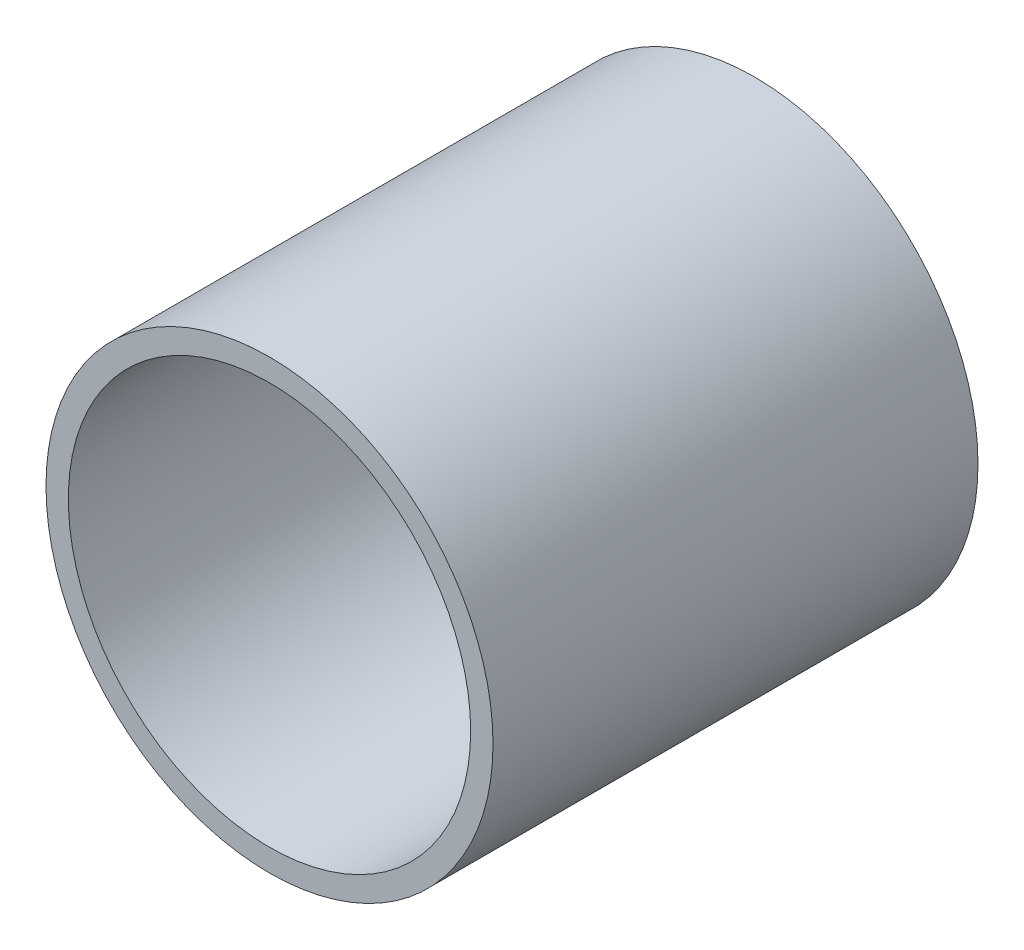
SolidWorks part; units mm, degrees
ref_plane "Front Plane" through (0, 0, 0) normal (0, 0, 1) x (1, 0, 0)
ref_plane "Top Plane" through (0, 0, 0) normal (0, 1, 0) x (1, 0, 0)
ref_plane "Right Plane" through (0, 0, 0) normal (1, 0, 0) x (0, 0, -1)
sketch "Sketch1" plane through (0, 0, 0) normal (0, 0, 1) x (1, 0, 0)
  circle A0 centre (0, 0) radius 90
  circle A1 centre (0, 0) radius 100
  dimension "D1" = 180
  dimension "D2" = 10
extrude "Boss-Extrude1" add sketch "Sketch1" along normal blind 217
